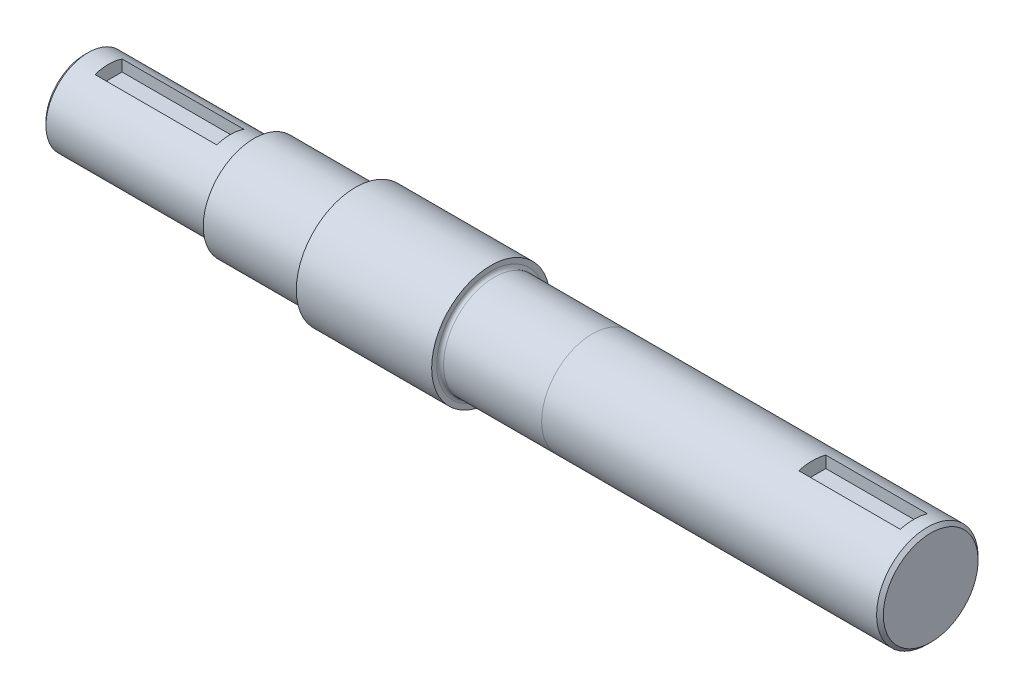
SolidWorks part; units mm, degrees
material "AISI 1045 Steel, cold drawn"
ref_plane "Front Plane" through (0, 0, 0) normal (0, 0, 1) x (1, 0, 0)
ref_plane "Top Plane" through (0, 0, 0) normal (0, 1, 0) x (1, 0, 0)
ref_plane "Right Plane" through (0, 0, 0) normal (1, 0, 0) x (0, 0, -1)
sketch "Sketch1" plane through (0, 0, 0) normal (0, 0, 1) x (1, 0, 0)
  line L0 (0, 0) -> (125.5875, 0) construction
  line L1 (0, 0) -> (0, 12.5)
  line L2 (0, 12.5) -> (50, 12.5)
  line L3 (50, 12.5) -> (50, 15)
  line L4 (50, 15) -> (80, 15)
  line L5 (80, 15) -> (80, 17.5)
  line L6 (80, 17.5) -> (120, 17.5)
  line L7 (120, 17.5) -> (120, 15)
  line L8 (120, 15) -> (250, 15)
  line L9 (250, 15) -> (250, 0)
  line L10 (250, 0) -> (0, 0)
  dimension "D1" = 12.5
  dimension "D2" = 50
  dimension "D3" = 2.5
  dimension "D4" = 30
  dimension "D5" = 2.5
  dimension "D6" = 40
  dimension "D7" = 2.5
  dimension "D8" = 130
revolve "Revolve1" add sketch "Sketch1" angle 360 about L0
ref_plane "Plane1" through (0, 8.5, 0) normal (0, 1, 0) x (1, 0, 0)
sketch "Sketch2" plane through (0, 8.5, 0) normal (0, 1, 0) x (1, 0, 0)
  line L0 (0, 12.5) -> (0, -12.5) construction
  line L2 (7, 4) -> (43, 4)
  line L3 (7, 4) -> (7, -4)
  line L4 (7, -4) -> (43, -4)
  line L5 (43, 4) -> (43, -4)
  point P7 (7, 0)
  dimension "D1" = 36
  dimension "D2" = 8
  dimension "D3" = 7
extrude "Cut-Extrude2" cut sketch "Sketch2" along normal through all contours L2 L5 L4 L3
ref_plane "Plane2" through (0, 11, 0) normal (0, 1, 0) x (1, 0, 0)
sketch "Sketch3" plane through (0, 11, 0) normal (0, 1, 0) x (1, 0, 0)
  line L0 (250, -15) -> (250, 15) construction
  line L3 (245, 4) -> (215, 4)
  line L4 (245, 4) -> (245, -4)
  line L5 (245, -4) -> (215, -4)
  line L6 (215, 4) -> (215, -4)
  point P3 (245, 0)
  dimension "D1" = 5
  dimension "D2" = 8
  dimension "D3" = 30
extrude "Cut-Extrude3" cut sketch "Sketch3" along normal through all
fillet "Fillet1" radius 1 3 edges at (120, 0, 15) (80, 0, 15) (50, 0, 12.5)
chamfer "Chamfer1" distance 1 angle 45 2 edges at (0, 0, 12.5) (250, 0, 15)
ref_plane "Plane3" through (150, 0, 0) normal (1, 0, 0) x (0, 0, -1)
split line "Split Line1"
